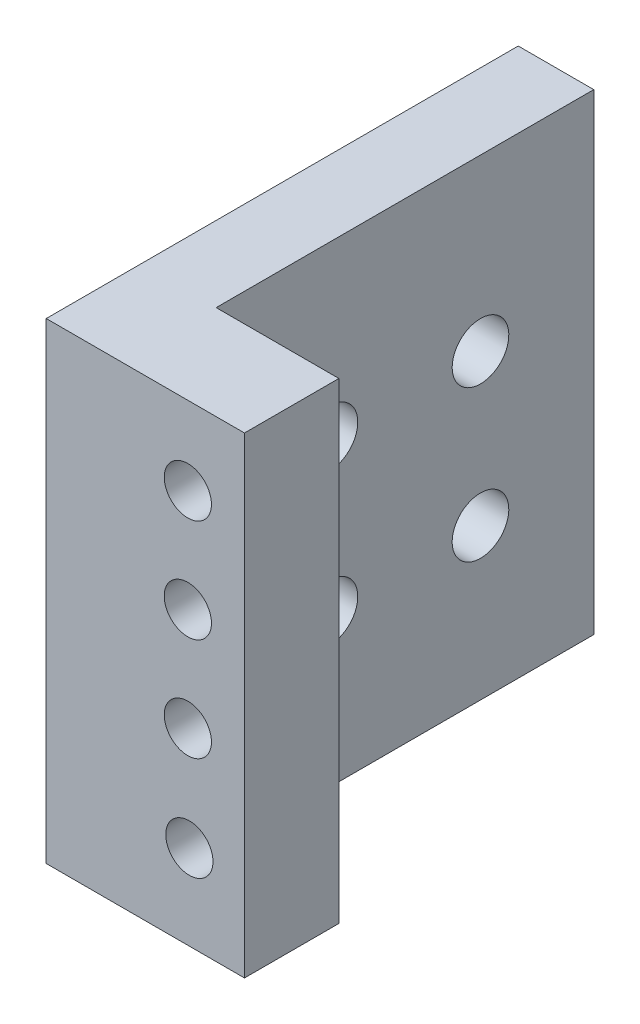
SolidWorks part; units mm, degrees
ref_plane "前视基准面" through (0, 0, 0) normal (0, 0, 1) x (1, 0, 0)
ref_plane "上视基准面" through (0, 0, 0) normal (0, 1, 0) x (1, 0, 0)
ref_plane "右视基准面" through (0, 0, 0) normal (1, 0, 0) x (0, 0, -1)
sketch "草图1" plane through (0, 0, 0) normal (0, 0, 1) x (1, 0, 0)
  line L0 (-3.5812, -8.028) -> (-3.5812, -12.6119)
  line L1 (-3.5812, 12.3881) -> (2.9188, 12.3881)
  line L2 (-3.5812, 12.3881) -> (-3.5812, -8.028)
  line L4 (2.9188, 12.3881) -> (2.9188, -6.6419)
  line L5 (-0.0812, -6.5) -> (-0.0812, 9.528) construction
  line L6 (-3.5812, 2.1801) -> (2.4188, 2.1801) construction
  line L7 (-3.5812, -12.6119) -> (2.9188, -12.6119)
  line L8 (2.9188, -12.6119) -> (2.9188, -6.6419)
  circle A0 centre (-0.0812, 8.2375) radius 1.25
  circle A1 centre (-0.0812, 2.7875) radius 1.25
  circle A2 centre (-0.0812, -2.6625) radius 1.25
  circle A3 centre (-0.0008, -8.1119) radius 1.25
  point P0 (0, 0)
  dimension "D3" = 2.5
  dimension "D4" = 2.5
  dimension "D5" = 2.5
  dimension "D1" = 2.5
  dimension "D2" = 4.5
  dimension "D6" = 5.45
  dimension "D7" = 6.5
  dimension "D8" = 5.45
  dimension "D9" = 5.45
  dimension "D10" = 3
  dimension "D11" = 25
extrude "凸台-拉伸1" add sketch "草图1" along normal blind 5
sketch "草图2" plane through (-3.5812, 0, 0) normal (-1, 0, 0) x (0, 0, 1)
  line L1 (0, 12.3881) -> (5, 12.3881)
  line L2 (0, 12.3881) -> (0, -12.6119)
  line L3 (0, -12.6119) -> (5, -12.6119)
  line L4 (5, 12.3881) -> (5, -12.6119)
extrude "凸台-拉伸2" add sketch "草图2" along normal blind 4
sketch "草图3" plane through (0, 0, 0) normal (0, 0, -1) x (-1, 0, 0)
  line L0 (-2.9188, 12.3881) -> (7.5812, 12.3881) construction
  line L1 (3.5812, 12.3881) -> (7.5812, 12.3881)
  line L2 (3.5812, 12.3881) -> (3.5812, -12.6119)
  line L3 (3.5812, -12.6119) -> (7.5812, -12.6119)
  line L4 (7.5812, 12.3881) -> (7.5812, -12.6119)
  line L5 (7.5812, 12.3881) -> (7.5812, -12.6119) construction
  line L6 (7.5812, -12.6119) -> (-2.9188, -12.6119) construction
  dimension "D1" = 4
extrude "凸台-拉伸3" add sketch "草图3" along normal blind 20 contours L2 L1 L4 L3
sketch "草图4" plane through (-3.5812, 0, 0) normal (1, 0, 0) x (0, 0, -1)
  line L0 (-0.5142, -0.6119) -> (22.6758, -0.6119) construction
  line L1 (10, 9.3991) -> (10, -15.8743) construction
  line L2 (20, 12.3881) -> (0, 12.3881) construction
  circle A0 centre (6, 3.3881) radius 1.5
  circle A1 centre (14, 3.3881) radius 1.5
  circle A2 centre (14, -4.6119) radius 1.5
  circle A3 centre (6, -4.6119) radius 1.5
  dimension "D1" = 3
  dimension "D2" = 4
  dimension "D3" = 4
  dimension "D4" = 9
extrude "切除-拉伸1" cut sketch "草图4" against normal blind 20
